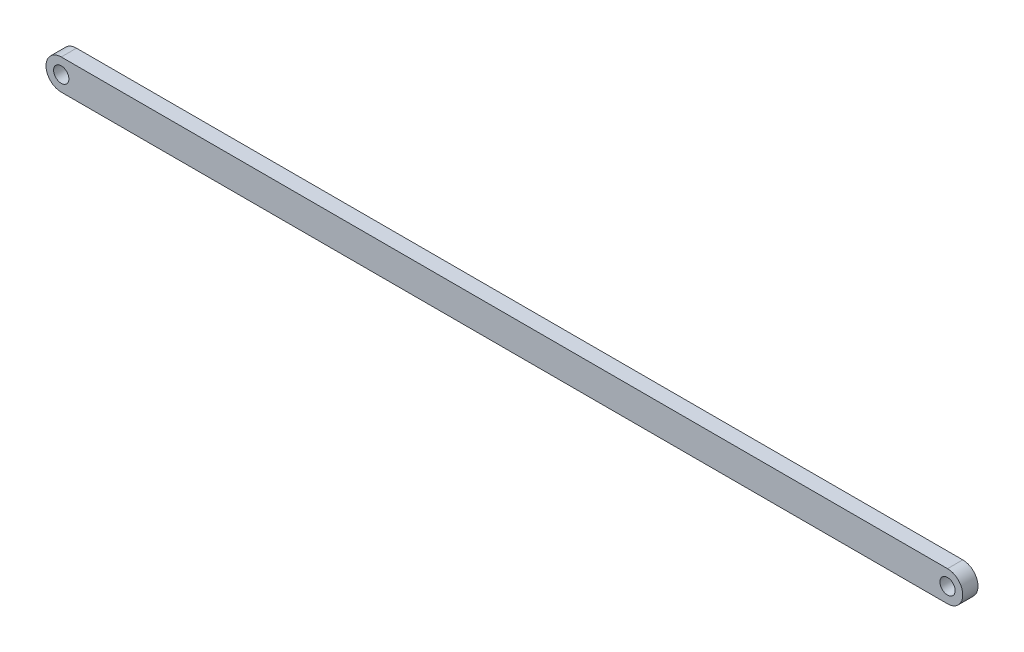
SolidWorks part; units mm, degrees
ref_plane "Plano frontal" through (0, 0, 0) normal (0, 0, 1) x (1, 0, 0)
ref_plane "Plano superior" through (0, 0, 0) normal (0, 1, 0) x (1, 0, 0)
ref_plane "Plano direito" through (0, 0, 0) normal (1, 0, 0) x (0, 0, -1)
sketch "Esboço1" plane through (0, 0, 0) normal (0, 0, 1) x (1, 0, 0)
  line L0 (0, 0) -> (0, 5) construction
  line L1 (-145.38, 5) -> (145.38, 5)
  line L2 (-145.38, 0) -> (145.38, 0) construction
  line L3 (-145.38, -5) -> (145.38, -5)
  arc A0 (-145.38, 5) -> (-145.38, -5) centre (-145.38, 0) ccw
  arc A1 (145.38, 5) -> (145.38, -5) centre (145.38, 0) cw
  circle A2 centre (-145.38, 0) radius 2.5
  circle A3 centre (145.38, 0) radius 2.5
  point P5 (0, 5)
  dimension "D2" = 10
  dimension "D1" = 290.76
extrude "Ressalto-extrusão1" add sketch "Esboço1" along normal blind 5
